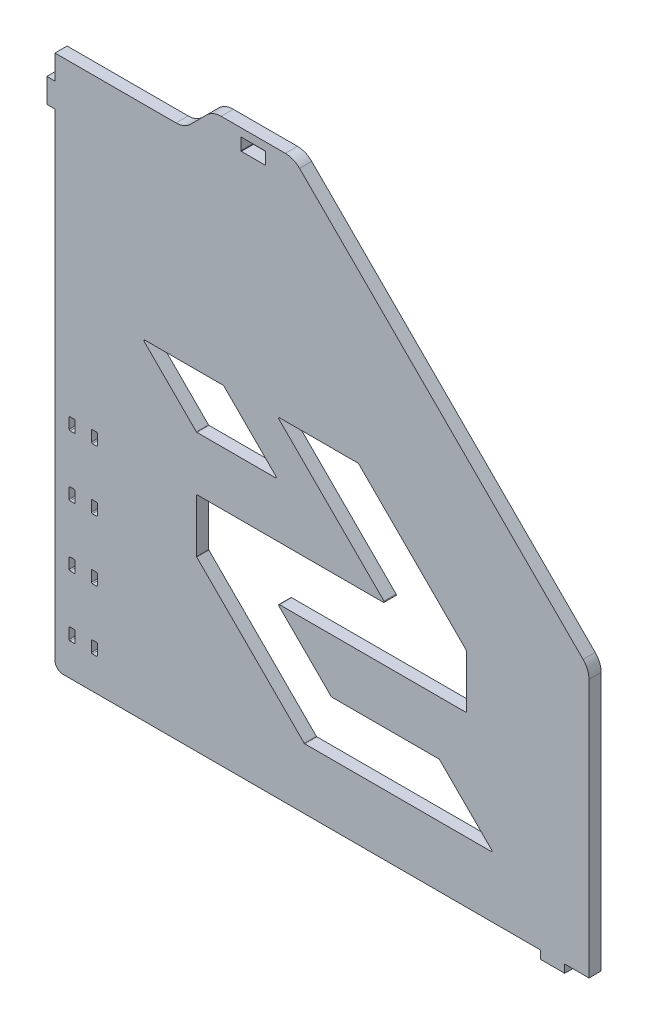
SolidWorks part; units mm, degrees
ref_plane "Front Plane" through (0, 0, 0) normal (0, 0, 1) x (1, 0, 0)
ref_plane "Top Plane" through (0, 0, 0) normal (0, 1, 0) x (1, 0, 0)
ref_plane "Right Plane" through (0, 0, 0) normal (1, 0, 0) x (0, 0, -1)
sketch "Sketch1" plane through (0, 0, 0) normal (0, 0, 1) x (1, 0, 0)
  line L0 (-66, 0) -> (66, 0) construction
  line L1 (-66, 65) -> (66, 65)
  line L2 (-66, 65) -> (-66, -65)
  line L3 (-66, -65) -> (66, -65)
  line L4 (66, 65) -> (66, -65)
  line L5 (-66, 65) -> (66, -65) construction
  line L6 (-66, -65) -> (66, 65) construction
  line L7 (-66, -65) -> (66, -65)
  line L8 (-66, -65) -> (-66, -67)
  line L9 (-66, -67) -> (66, -67)
  line L10 (66, -65) -> (66, -67)
  line L11 (0, 65) -> (0, -65) construction
  line L13 (-66, 59) -> (-68, 59)
  line L14 (-66, 59) -> (-66, 53)
  line L15 (-66, 53) -> (-68, 53)
  line L16 (-68, 59) -> (-68, 53)
  line L25 (0, 65) -> (66, -1)
  line L26 (0, -67) -> (0, 65) construction
  line L27 (60, -67) -> (54, -67)
  line L28 (60, -67) -> (60, -69)
  line L29 (60, -69) -> (54, -69)
  line L30 (54, -67) -> (54, -69)
  line L31 (0, 65) -> (-7, 72)
  line L32 (-7, 72) -> (-27, 72)
  line L33 (-27, 72) -> (-34, 65)
  line L34 (-17, 72) -> (-17, 65) construction
  line L35 (-20.025, 69.925) -> (-20.025, 67.075)
  line L36 (-20, 70) -> (-14, 70)
  line L37 (-20, 70) -> (-20, 67)
  line L38 (-20, 67) -> (-14, 67)
  line L39 (-14, 70) -> (-14, 67)
  line L40 (-20, 70) -> (-14, 67) construction
  line L41 (-20, 67) -> (-14, 70) construction
  line L42 (-19.925, 66.975) -> (-14.075, 66.975)
  line L43 (-13.975, 69.925) -> (-13.975, 67.075)
  line L44 (-19.925, 70.025) -> (-14.075, 70.025)
  line L45 (-20.025, 70.025) -> (-20.025, 66.975) construction
  line L46 (-20.025, 66.975) -> (-13.975, 66.975) construction
  line L47 (-13.975, 70.025) -> (-13.975, 66.975) construction
  line L48 (-20.025, 70.025) -> (-13.975, 70.025) construction
  arc A0 (-20.025, 67.075) -> (-19.925, 66.975) centre (-19.925, 67.075) ccw
  arc A1 (-14.075, 66.975) -> (-13.975, 67.075) centre (-14.075, 67.075) ccw
  arc A2 (-13.975, 69.925) -> (-14.075, 70.025) centre (-14.075, 69.925) ccw
  arc A3 (-20.025, 69.925) -> (-19.925, 70.025) centre (-19.925, 69.925) cw
  point P0 (0, 0)
  point P23 (-17, 68.5)
  dimension "D12" = 0.1
  dimension "D1" = 130
  dimension "D2" = 45
  dimension "D3" = 2
  dimension "D4" = 2
  dimension "D5" = 6
  dimension "D6" = 6
  dimension "D7" = 6
  dimension "D8" = 3
  dimension "D9" = 2
  dimension "D10" = 20
  dimension "D11" = 0.025
extrude "Boss-Extrude1" add sketch "Sketch1" along normal blind 3
sketch "Sketch6" plane through (0, 0, 0) normal (0, 0, -1) x (-1, 0, 0)
  line L2 (-42.3333, -38.6667) -> (-42.3333, -52) construction
  line L3 (57.6667, 1.3333) -> (57.6667, 14.6667) construction
  line L4 (-2.3333, -38.6667) -> (-2.3333, 1.3333) construction
  line L5 (66, 53) -> (66, -67) construction
  line L7 (66, -67) -> (-54, -67) construction
  line L19 (-75.6667, -52) -> (4.3333, -52)
  line L20 (-75.6667, -52) -> (-9, 14.6667)
  line L21 (4.3333, -52) -> (71, 14.6667)
  line L22 (-9, 14.6667) -> (71, 14.6667)
  line L23 (-55.6667, -52) -> (11, 14.6667)
  line L24 (-35.6667, -52) -> (31, 14.6667)
  line L25 (-15.6667, -52) -> (51, 14.6667)
  line L26 (-62.3333, -38.6667) -> (17.6667, -38.6667)
  line L27 (-49, -25.3333) -> (31, -25.3333)
  line L28 (-35.6667, -12) -> (44.3333, -12)
  line L29 (-22.3333, 1.3333) -> (57.6667, 1.3333)
  line L30 (17.6667, -38.6667) -> (31, -38.6667) construction
  line L31 (31, -25.3333) -> (44.3333, -25.3333) construction
  line L32 (31, -25.3333) -> (31, -38.6667) construction
  line L33 (57.6667, -12) -> (57.6667, 1.3333) construction
  line L34 (44.3333, -12) -> (44.3333, -25.3333) construction
  line L35 (44.3333, -12) -> (57.6667, -12) construction
  line L36 (17.6667, -38.6667) -> (17.6667, -52) construction
  line L37 (17.6667, -52) -> (4.3333, -52) construction
  line L38 (31, -25.3333) -> (31, -12)
  line L39 (31, -12) -> (31, 1.3333) construction
  line L40 (31, 1.3333) -> (44.3333, 14.6667)
  line L41 (11, 1.3333) -> (24.3333, 14.6667)
  line L42 (17.6667, 8) -> (37.6667, 8) construction
  line L43 (4.3333, 8) -> (-15.6667, 8) construction
  line L44 (-35.6667, -12) -> (-35.6667, -25.3333)
  line L45 (-29, -38.6667) -> (-42.3333, -52)
  dimension "D1" = 15
  dimension "D2" = 15
  dimension "D4" = 45
  dimension "D5" = 80
  dimension "D7" = 4
extrude "Cut-Extrude2" cut sketch "Sketch6" against normal up to next contours L29 L40 L22 L24 | L41 L29 L24 L22 | L20 L29 L23 L22 | L29 L20 L28 L23 | L28 L44 L27 L23 | L28 L23 L27 L24 | L28 L24 L27 L25 | L27 L38 L28 L25 | L27 L25 L26 L21 | L26 L25 L19 L21 | L26 L24 L19 L25 | L26 L45 L19 L24
sketch "Sketch7" plane through (0, 0, 3) normal (0, 0, 1) x (1, 0, 0)
  line L0 (-66, -67) -> (54, -67) construction
  line L1 (-61, 65) -> (-57, 65)
  line L2 (-61, 65) -> (-61, -67)
  line L3 (-61, -67) -> (-57, -67)
  line L4 (-57, 65) -> (-57, -67)
  line L5 (-61, 65) -> (-57, -67) construction
  line L6 (-61, -67) -> (-57, 65) construction
  line L7 (-66, 65) -> (-34, 65) construction
  line L8 (-59, 65) -> (-59, -67) construction
  line L9 (-66, 53) -> (-66, -67) construction
  line L10 (-57, -58.75) -> (-57, -56.25)
  line L11 (-61.25, -59) -> (-62.25, -59)
  line L12 (-61, -58.75) -> (-61, -56.25)
  line L13 (-61.25, -56) -> (-62.25, -56)
  line L14 (-62.5, -58.75) -> (-62.5, -56.25)
  line L15 (-56.75, -56) -> (-55.75, -56)
  line L16 (-55.5, -58.75) -> (-55.5, -56.25)
  line L17 (-56.75, -59) -> (-55.75, -59)
  line L18 (-61.25, -44) -> (-62.25, -44)
  line L19 (-62.5, -43.75) -> (-62.5, -41.25)
  line L20 (-61.25, -41) -> (-62.25, -41)
  line L21 (-61, -43.75) -> (-61, -41.25)
  line L22 (-56.75, -44) -> (-55.75, -44)
  line L23 (-55.5, -43.75) -> (-55.5, -41.25)
  line L24 (-56.75, -41) -> (-55.75, -41)
  line L25 (-57, -43.75) -> (-57, -41.25)
  line L26 (-61.25, -29) -> (-62.25, -29)
  line L27 (-62.5, -28.75) -> (-62.5, -26.25)
  line L28 (-61.25, -26) -> (-62.25, -26)
  line L29 (-61, -28.75) -> (-61, -26.25)
  line L30 (-56.75, -29) -> (-55.75, -29)
  line L31 (-55.5, -28.75) -> (-55.5, -26.25)
  line L32 (-56.75, -26) -> (-55.75, -26)
  line L33 (-57, -28.75) -> (-57, -26.25)
  line L42 (-62.5, -57.5) -> (-61, -57.5) construction
  line L43 (-61.25, -14) -> (-62.25, -14)
  line L44 (-62.5, -13.75) -> (-62.5, -11.25)
  line L45 (-61.25, -11) -> (-62.25, -11)
  line L46 (-61, -13.75) -> (-61, -11.25)
  line L47 (-56.75, -14) -> (-55.75, -14)
  line L48 (-55.5, -13.75) -> (-55.5, -11.25)
  line L49 (-56.75, -11) -> (-55.75, -11)
  line L50 (-57, -13.75) -> (-57, -11.25)
  arc A0 (-62.25, -59) -> (-62.5, -58.75) centre (-62.25, -58.75) cw
  arc A1 (-61.25, -59) -> (-61, -58.75) centre (-61.25, -58.75) ccw
  arc A2 (-61, -56.25) -> (-61.25, -56) centre (-61.25, -56.25) ccw
  arc A3 (-62.25, -56) -> (-62.5, -56.25) centre (-62.25, -56.25) ccw
  arc A4 (-56.75, -59) -> (-57, -58.75) centre (-56.75, -58.75) cw
  arc A5 (-57, -56.25) -> (-56.75, -56) centre (-56.75, -56.25) cw
  arc A6 (-55.75, -56) -> (-55.5, -56.25) centre (-55.75, -56.25) cw
  arc A7 (-55.75, -59) -> (-55.5, -58.75) centre (-55.75, -58.75) ccw
  arc A8 (-62.25, -44) -> (-62.5, -43.75) centre (-62.25, -43.75) cw
  arc A9 (-62.25, -41) -> (-62.5, -41.25) centre (-62.25, -41.25) ccw
  arc A10 (-61, -41.25) -> (-61.25, -41) centre (-61.25, -41.25) ccw
  arc A11 (-61.25, -44) -> (-61, -43.75) centre (-61.25, -43.75) ccw
  arc A12 (-55.75, -44) -> (-55.5, -43.75) centre (-55.75, -43.75) ccw
  arc A13 (-55.75, -41) -> (-55.5, -41.25) centre (-55.75, -41.25) cw
  arc A14 (-57, -41.25) -> (-56.75, -41) centre (-56.75, -41.25) cw
  arc A15 (-56.75, -44) -> (-57, -43.75) centre (-56.75, -43.75) cw
  arc A16 (-62.25, -29) -> (-62.5, -28.75) centre (-62.25, -28.75) cw
  arc A17 (-62.25, -26) -> (-62.5, -26.25) centre (-62.25, -26.25) ccw
  arc A18 (-61, -26.25) -> (-61.25, -26) centre (-61.25, -26.25) ccw
  arc A19 (-61.25, -29) -> (-61, -28.75) centre (-61.25, -28.75) ccw
  arc A20 (-55.75, -29) -> (-55.5, -28.75) centre (-55.75, -28.75) ccw
  arc A21 (-55.75, -26) -> (-55.5, -26.25) centre (-55.75, -26.25) cw
  arc A22 (-57, -26.25) -> (-56.75, -26) centre (-56.75, -26.25) cw
  arc A23 (-56.75, -29) -> (-57, -28.75) centre (-56.75, -28.75) cw
  arc A24 (-62.25, -14) -> (-62.5, -13.75) centre (-62.25, -13.75) cw
  arc A25 (-62.25, -11) -> (-62.5, -11.25) centre (-62.25, -11.25) ccw
  arc A26 (-61, -11.25) -> (-61.25, -11) centre (-61.25, -11.25) ccw
  arc A27 (-61.25, -14) -> (-61, -13.75) centre (-61.25, -13.75) ccw
  arc A28 (-55.75, -14) -> (-55.5, -13.75) centre (-55.75, -13.75) ccw
  arc A29 (-55.75, -11) -> (-55.5, -11.25) centre (-55.75, -11.25) cw
  arc A30 (-57, -11.25) -> (-56.75, -11) centre (-56.75, -11.25) cw
  arc A31 (-56.75, -14) -> (-57, -13.75) centre (-56.75, -13.75) cw
  point P0 (-59, -1)
  point P19 (-62.5, -59)
  point P22 (-61, -59)
  point P25 (-61, -56)
  point P28 (-62.5, -56)
  dimension "D6" = 0.25
  dimension "D1" = 4
  dimension "D2" = 7
  dimension "D3" = 3
  dimension "D4" = 1.5
  dimension "D5" = 9.5
  dimension "D8" = 15
  dimension "D7" = 4
extrude "Cut-Extrude3" cut sketch "Sketch7" against normal up to next contours L13 A3 L14 A0 L11 A1 L2 A2 | L17 A7 L16 A6 L15 A5 L4 A4 | A15 L22 A12 L23 A13 L24 A14 L4 | L18 A11 L2 A10 L20 A9 L19 A8 | L26 A19 L2 A18 L28 A17 L27 A16 | A23 L30 A20 L31 A21 L32 A22 L4 | L43 A27 L2 A26 L45 A25 L44 A24 | A31 L47 A28 L48 A29 L49 A30 L4
fillet "Fillet1" radius 5 4 edges at (66, -1, 1.5) (-34, 65, 1.5) (-27, 72, 1.5) (-7, 72, 1.5)
sketch "Sketch5" plane through (0, 0, 3) normal (0, 0, 1) x (1, 0, 0)
  line L2 (-51, -38.6667) -> (-51, -52) construction
  line L3 (49, 1.3333) -> (49, 14.6667) construction
  line L4 (-11, -38.6667) -> (-11, 1.3333) construction
  line L5 (-66, -67) -> (54, -67) construction
  line L7 (-66, 53) -> (-66, -67) construction
  line L19 (-84.3333, -52) -> (-4.3333, -52)
  line L20 (-84.3333, -52) -> (-17.6667, 14.6667)
  line L21 (-4.3333, -52) -> (62.3333, 14.6667)
  line L22 (-17.6667, 14.6667) -> (62.3333, 14.6667)
  line L23 (-64.3333, -52) -> (2.3333, 14.6667)
  line L24 (-44.3333, -52) -> (22.3333, 14.6667)
  line L25 (-24.3333, -52) -> (42.3333, 14.6667)
  line L26 (-71, -38.6667) -> (9, -38.6667)
  line L27 (-57.6667, -25.3333) -> (22.3333, -25.3333)
  line L28 (-44.3333, -12) -> (35.6667, -12)
  line L29 (-31, 1.3333) -> (49, 1.3333)
  line L30 (9, -38.6667) -> (22.3333, -38.6667) construction
  line L31 (22.3333, -25.3333) -> (35.6667, -25.3333) construction
  line L32 (22.3333, -25.3333) -> (22.3333, -38.6667) construction
  line L33 (49, -12) -> (49, 1.3333) construction
  line L34 (35.6667, -12) -> (35.6667, -25.3333) construction
  line L35 (35.6667, -12) -> (49, -12) construction
  line L36 (9, -38.6667) -> (9, -52) construction
  line L37 (9, -52) -> (-4.3333, -52) construction
  line L38 (22.3333, -25.3333) -> (22.3333, -12)
  line L39 (22.3333, -12) -> (22.3333, 1.3333) construction
  line L40 (22.3333, 1.3333) -> (35.6667, 14.6667)
  line L41 (2.3333, 1.3333) -> (15.6667, 14.6667)
  line L42 (9, 8) -> (29, 8) construction
  line L43 (-4.3333, 8) -> (-24.3333, 8) construction
  line L44 (-44.3333, -12) -> (-44.3333, -25.3333)
  line L45 (-37.6667, -38.6667) -> (-51, -52)
  dimension "D1" = 15
  dimension "D2" = 15
  dimension "D4" = 45
  dimension "D5" = 80
  dimension "D7" = 4
extrude "Cut-Extrude1" [suppressed] cut sketch "Sketch5" against normal up to next contours L29 L40 L22 L24 | L41 L29 L24 L22 | L20 L29 L23 L22 | L29 L20 L28 L23 | L28 L44 L27 L23 | L28 L23 L27 L24 | L28 L24 L27 L25 | L27 L38 L28 L25 | L27 L25 L26 L21 | L26 L25 L19 L21 | L26 L24 L19 L25 | L26 L45 L19 L24
fillet "Fillet2" radius 2 1 edges at (-66, -67, 1.5)
fillet "Fillet3" [suppressed] radius 0.2
fillet "Fillet4" radius 0.2 16 edges at (42.3333, -52, 1.5) (29, -38.6667, 1.5) (2.3333, -38.6667, 1.5) (-24.3333, 14.6667, 1.5) (-11, 1.3333, 1.5) (-31, 1.3333, 1.5) (-44.3333, 14.6667, 1.5) (-11, 14.6667, 1.5) (9, 14.6667, 1.5) (35.6667, -12, 1.5) (35.6667, -25.3333, 1.5) (-11, -25.3333, 1.5) (15.6667, -12, 1.5) (-31, -12, 1.5) (-31, -25.3333, 1.5) (-4.3333, -52, 1.5)
